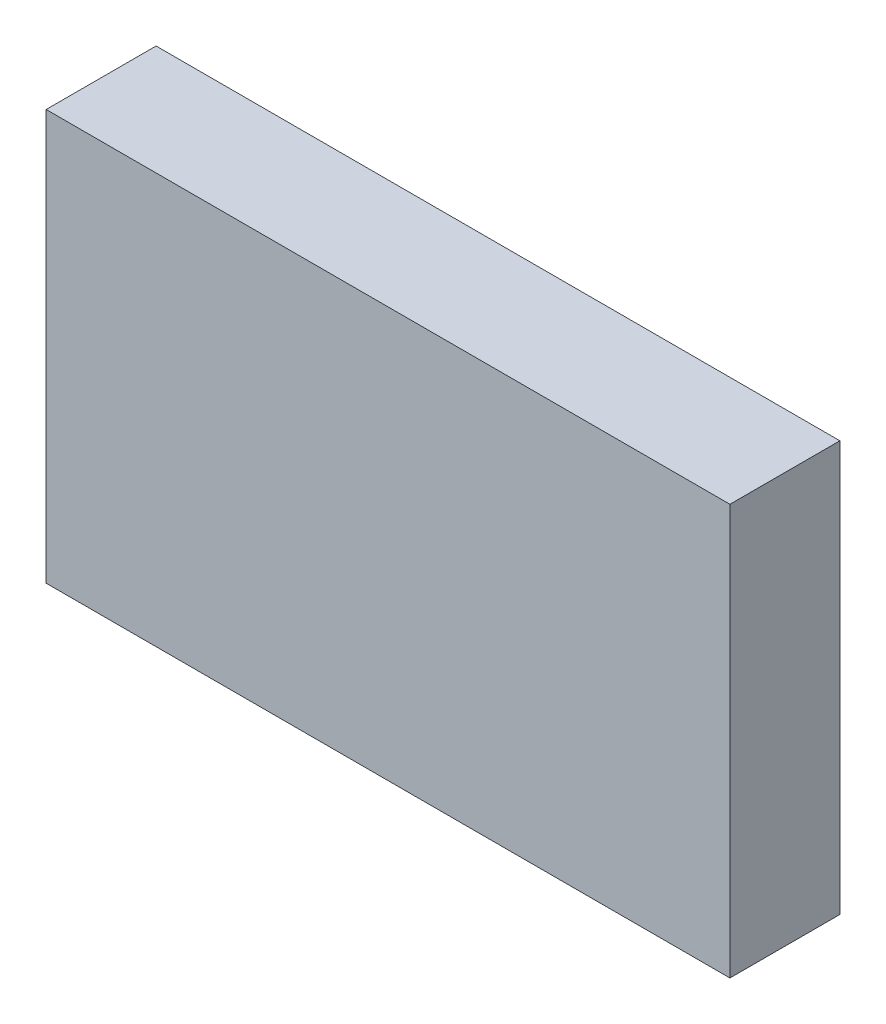
SolidWorks part; units mm, degrees
ref_plane "Front Plane" through (0, 0, 0) normal (0, 0, 1) x (1, 0, 0)
ref_plane "Top Plane" through (0, 0, 0) normal (0, 1, 0) x (1, 0, 0)
ref_plane "Right Plane" through (0, 0, 0) normal (1, 0, 0) x (0, 0, -1)
sketch "Sketch1" plane through (0, 0, 0) normal (0, 0, 1) x (1, 0, 0)
  line L1 (-12.5, 7.5) -> (12.5, 7.5)
  line L2 (-12.5, 7.5) -> (-12.5, -7.5)
  line L3 (-12.5, -7.5) -> (12.5, -7.5)
  line L4 (12.5, 7.5) -> (12.5, -7.5)
  line L5 (-12.5, 7.5) -> (12.5, -7.5) construction
  line L6 (-12.5, -7.5) -> (12.5, 7.5) construction
  point P0 (0, 0)
  dimension "D1" = 25
  dimension "D2" = 15
extrude "Boss-Extrude1" add sketch "Sketch1" along normal blind 4.02
